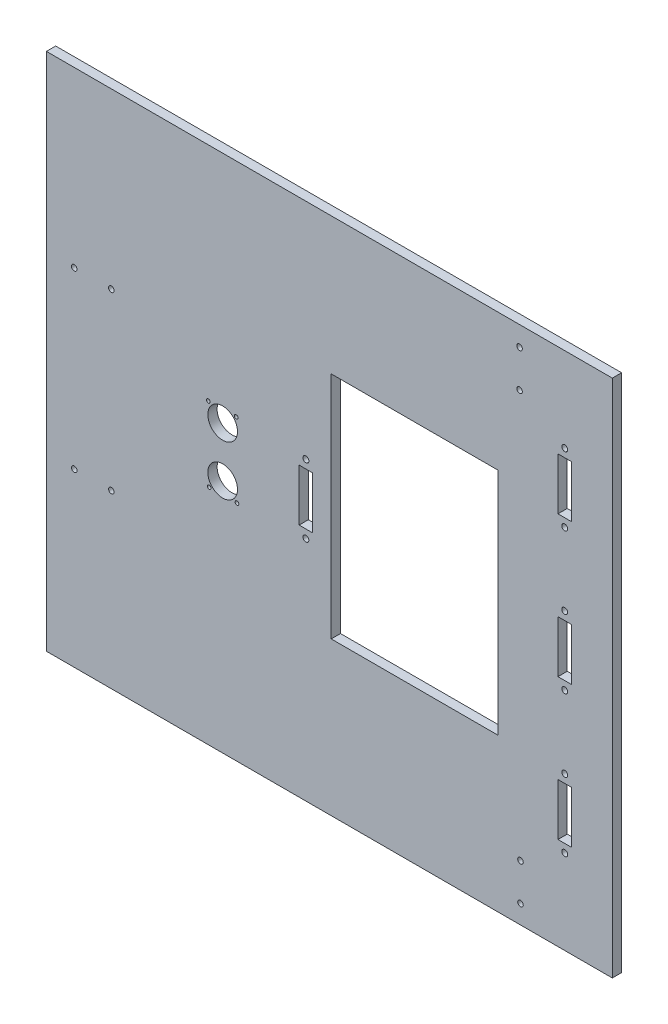
SolidWorks part; units mm, degrees
ref_plane "Plan de face" through (0, 0, 0) normal (0, 0, 1) x (1, 0, 0)
ref_plane "Plan de dessus" through (0, 0, 0) normal (0, 1, 0) x (1, 0, 0)
ref_plane "Plan de droite" through (0, 0, 0) normal (1, 0, 0) x (0, 0, -1)
sketch "Esquisse1" plane through (0, 0, 0) normal (0, 0, 1) x (1, 0, 0)
  line L1 (0, 0) -> (305, 0)
  line L2 (0, 0) -> (0, 280)
  line L3 (0, 280) -> (305, 280)
  line L4 (305, 0) -> (305, 280)
  dimension "D1" = 280
  dimension "D2" = 305
extrude "Boss.-Extru.1" add sketch "Esquisse1" along normal blind 5
sketch "Esquisse2" plane through (0, 0, 5) normal (0, 0, 1) x (1, 0, 0)
  line L0 (305, 0) -> (305, 280) construction
  line L1 (153.5, 206.22) -> (243.5, 206.22)
  line L2 (153.5, 206.22) -> (153.5, 82.52)
  line L3 (153.5, 82.52) -> (243.5, 82.52)
  line L4 (243.5, 206.22) -> (243.5, 82.52)
  line L5 (305, 280) -> (0, 280) construction
  line L6 (0, 0) -> (305, 0) construction
  point P10 (153.5, 144.37)
  dimension "D1" = 61.5
  dimension "D2" = 73.78
  dimension "D3" = 82.52
  dimension "D4" = 90
extrude "Enlèv. mat.-Extru.1" cut sketch "Esquisse2" against normal blind 5
sketch "Esquisse3" plane through (0, 0, 0) normal (0, 0, -1) x (-1, 0, 0)
  circle A0 centre (-15, 92.5) radius 1.5
  circle A1 centre (-35, 92.5) radius 1.5
  circle A2 centre (-35, 186.5) radius 1.5
  circle A3 centre (-15, 186.5) radius 1.5
  circle A4 centre (-255, 249.4) radius 1.5
  circle A5 centre (-255, 269.4) radius 1.5
  circle A6 centre (-255.5, 10) radius 1.5
  circle A7 centre (-255.5, 30) radius 1.5
  dimension "D1" = 3
extrude "Enlèv. mat.-Extru.2" cut sketch "Esquisse3" against normal through all
sketch "Esquisse4" plane through (0, 0, 5) normal (0, 0, 1) x (1, 0, 0)
  line L0 (305, 0) -> (305, 280) construction
  line L1 (275.7, 50) -> (283, 50)
  line L2 (275.7, 50) -> (275.7, 78)
  line L3 (275.7, 78) -> (283, 78)
  line L4 (283, 50) -> (283, 78)
  line L5 (275.7, 126) -> (283, 126)
  line L6 (275.7, 126) -> (275.7, 154)
  line L7 (275.7, 154) -> (283, 154)
  line L8 (283, 126) -> (283, 154)
  line L9 (275.7, 202) -> (283, 202)
  line L10 (275.7, 202) -> (275.7, 230)
  line L11 (275.7, 230) -> (283, 230)
  line L12 (283, 202) -> (283, 230)
  line L13 (0, 0) -> (305, 0) construction
  line L14 (305, 280) -> (0, 280) construction
  line L15 (153.5, 206.22) -> (153.5, 82.52) construction
  line L16 (136.2, 127) -> (143.5, 127)
  line L17 (136.2, 127) -> (136.2, 155)
  line L18 (136.2, 155) -> (143.5, 155)
  line L19 (143.5, 127) -> (143.5, 155)
  line L20 (139.85, 117.3791) -> (139.85, 165.7171) construction
  line L21 (279.35, 33.1371) -> (279.35, 261.3707) construction
  circle A0 centre (139.85, 159.5) radius 1.6
  circle A1 centre (139.85, 122.5) radius 1.6
  circle A2 centre (279.35, 82.5) radius 1.6
  circle A3 centre (279.35, 45.5) radius 1.6
  circle A4 centre (279.35, 121.5) radius 1.6
  circle A5 centre (279.35, 158.5) radius 1.6
  circle A6 centre (279.35, 197.5) radius 1.6
  circle A7 centre (279.35, 234.5) radius 1.6
  point P12 (279.35, 50)
  point P13 (279.35, 126)
  point P14 (279.35, 154)
  point P15 (279.35, 230)
  point P18 (275.7, 140)
  dimension "D20" = 3.2
  dimension "D21" = 3.2
  dimension "D23" = 3.2
  dimension "D24" = 3.2
  dimension "D25" = 3.2
  dimension "D26" = 3.2
  dimension "D27" = 3.2
  dimension "D28" = 3.2
  dimension "D29" = 4.5
  dimension "D30" = 4.5
  dimension "D31" = 4.5
  dimension "D32" = 4.5
  dimension "D33" = 4.5
  dimension "D34" = 4.5
  dimension "D1" = 28
  dimension "D2" = 28
  dimension "D3" = 28
  dimension "D4" = 7.3
  dimension "D5" = 7.3
  dimension "D6" = 7.3
  dimension "D7" = 22
  dimension "D8" = 22
  dimension "D9" = 22
  dimension "D10" = 140
  dimension "D11" = 50
  dimension "D12" = 50
  dimension "D13" = 28
  dimension "D14" = 7.3
  dimension "D15" = 125
  dimension "D16" = 10
  dimension "D17" = 3.65
  dimension "D18" = 4.5
  dimension "D19" = 4.5
  dimension "D22" = 3.65
extrude "Enlèv. mat.-Extru.3" cut sketch "Esquisse4" against normal through all
sketch "Esquisse5" plane through (0, 0, 5) normal (0, 0, 1) x (1, 0, 0)
  line L0 (305, 0) -> (305, 280) construction
  line L1 (0, 0) -> (305, 0) construction
  circle A0 centre (95, 127) radius 8
  circle A1 centre (95, 154) radius 8
  circle A2 centre (87.7158, 120.4517) radius 1
  circle A3 centre (87.2842, 160.4517) radius 1
  circle A4 centre (102.2842, 160.5483) radius 1
  circle A5 centre (102.7158, 120.5483) radius 1
  dimension "D1" = 27
  dimension "D2" = 16
  dimension "D3" = 16
  dimension "D4" = 210
  dimension "D5" = 210
  dimension "D6" = 127
  dimension "D7" = 2
  dimension "D8" = 2
  dimension "D9" = 2
  dimension "D10" = 2
  dimension "D11" = 34.33
  dimension "D12" = 34.33
  dimension "D13" = 34.33
  dimension "D14" = 34.33
  dimension "D15" = 40
  dimension "D16" = 40
  dimension "D17" = 15
  dimension "D18" = 15
extrude "Enlèv. mat.-Extru.4" cut sketch "Esquisse5" against normal through all
